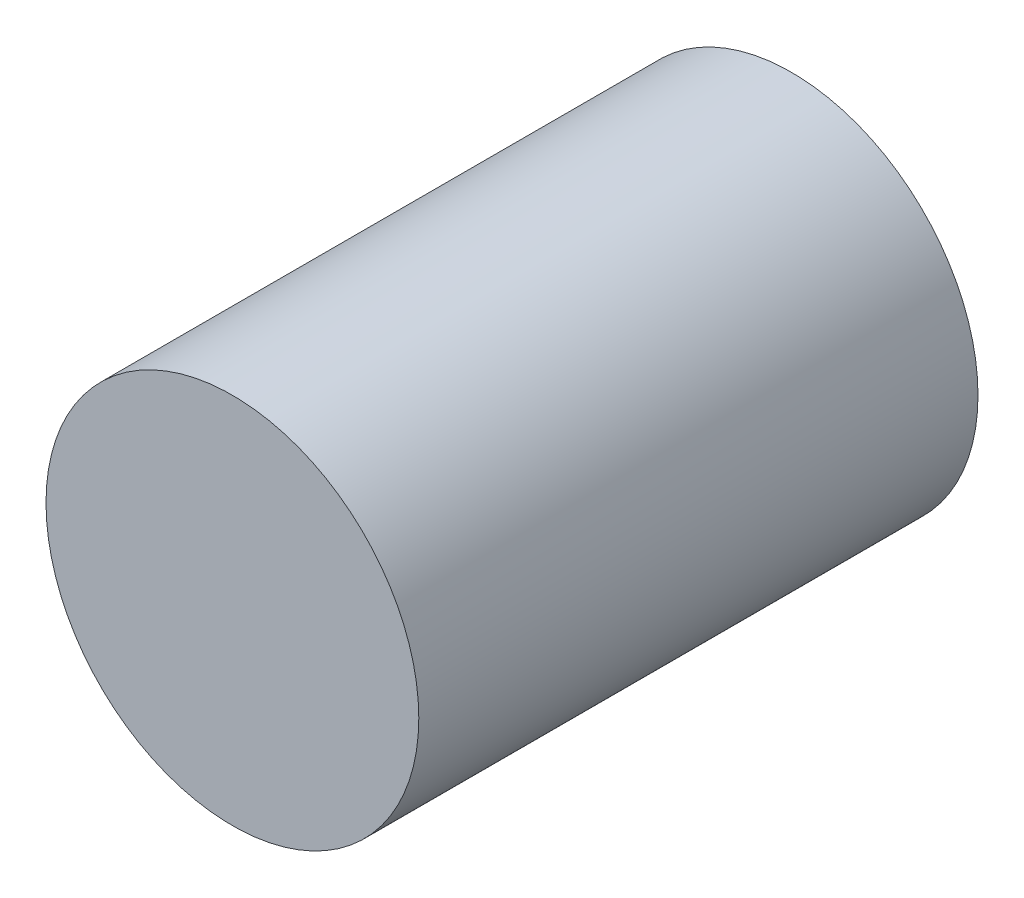
SolidWorks part; units mm, degrees
ref_plane "前视基准面" through (0, 0, 0) normal (0, 0, 1) x (1, 0, 0)
ref_plane "上视基准面" through (0, 0, 0) normal (0, 1, 0) x (1, 0, 0)
ref_plane "右视基准面" through (0, 0, 0) normal (1, 0, 0) x (0, 0, -1)
other "Configuration Table"
sketch "草图1" plane through (0, 0, 0) normal (0, 0, 1) x (1, 0, 0)
  circle A0 centre (0, 0) radius 8
extrude "凸台-拉伸1" add sketch "草图1" along normal blind 24
sketch "草图2" plane through (0, 0, 0) normal (0, 0, 1) x (1, 0, 0)
  circle A0 centre (0, 0) radius 22
sketch "草图3" plane through (0, 0, 0) normal (0, 0, 1) x (1, 0, 0)
  circle A0 centre (0, 0) radius 8
  circle A1 centre (0, 0) radius 22
sketch "草图4" plane through (0, 0, 0) normal (0, 0, 1) x (1, 0, 0)
  arc A0 (4.5201, 2.3619) -> (-5.1, 0) centre (0, 0) cw
sketch "草图5" plane through (0, 0, 0) normal (0, 0, 1) x (1, 0, 0)
  line L0 (18.3379, 4.1145) -> (17.0755, 3.0964)
  arc A0 (21.989, 0) -> (21.117, 6.1312) centre (0, 0) ccw
sketch "草图6" plane through (0, 0, 0) normal (0, 0, 1) x (1, 0, 0)
  line L0 (16.169, 9.5798) -> (15.0558, 9.9878)
  arc A0 (20.6981, 7.4557) -> (18.1979, 12.3627) centre (0, 0) ccw
  arc A1 (15.0558, 9.9878) -> (16.5873, 7.1621) centre (0, 0) ccw
sketch "草图7" plane through (0, 0, 0) normal (0, 0, 1) x (1, 0, 0)
  arc A0 (17.3811, 13.4869) -> (13.4869, 17.3811) centre (0, 0) ccw
  arc A1 (11.5624, 13.4869) -> (13.335, 11.7373) centre (0, 0) ccw
sketch "草图8" plane through (0, 0, 0) normal (0, 0, 1) x (1, 0, 0)
  arc A0 (12.3627, 18.1979) -> (7.4557, 20.6981) centre (0, 0) ccw
  arc A1 (7.4557, 16.0663) -> (9.0284, 15.2382) centre (0, 0) ccw
sketch "草图9" plane through (0, 0, 0) normal (0, 0, 1) x (1, 0, 0)
  arc A0 (6.1342, 21.1275) -> (0, 22) centre (0, 0) ccw
  arc A1 (0, 17.4237) -> (3.8145, 17.001) centre (0, 0) cw
sketch "草图10" plane through (0, 0, 0) normal (0, 0, 1) x (1, 0, 0)
  arc A0 (0, 21.989) -> (-6.1312, 21.117) centre (0, 0) ccw
  arc A1 (-3.8312, 17.0755) -> (0, 17.5) centre (0, 0) ccw
sketch "草图11" plane through (0, 0, 0) normal (0, 0, 1) x (1, 0, 0)
  arc A0 (-7.4557, 20.6981) -> (-12.3627, 18.1979) centre (0, 0) ccw
  arc A1 (-7.4557, 15.0558) -> (-6.66, 15.4243) centre (0, 0) cw
sketch "草图12" plane through (0, 0, 0) normal (0, 0, 1) x (1, 0, 0)
  arc A0 (-13.4869, 17.3811) -> (-17.3811, 13.4869) centre (0, 0) ccw
  arc A1 (-13.4869, 11.5624) -> (-11.7373, 13.335) centre (0, 0) ccw
sketch "草图13" plane through (0, 0, 0) normal (0, 0, 1) x (1, 0, 0)
  line L0 (-16.4574, 7.4557) -> (-15.8845, 8.6091)
  arc A0 (-18.1979, 12.3627) -> (-20.6981, 7.4557) centre (0, 0) ccw
  arc A1 (15.0558, 9.9878) -> (16.5873, 7.1621) centre (0, 0) ccw construction
  arc A2 (-16.4574, 7.4557) -> (-15.8845, 8.6091) centre (0, 0) ccw
sketch "草图14" plane through (0, 0, 0) normal (0, 0, 1) x (1, 0, 0)
  arc A0 (-21.1275, 6.1342) -> (-22, 0) centre (0, 0) ccw
  arc A1 (-17.4237, 0) -> (-17.001, 3.8145) centre (0, 0) cw
sketch "草图15" plane through (0, 0, 0) normal (0, 0, 1) x (1, 0, 0)
  arc A0 (-21.989, 0) -> (-21.117, -6.1312) centre (0, 0) ccw
  arc A1 (-17.0755, -3.8312) -> (-17.5, 0) centre (0, 0) ccw
sketch "草图16" plane through (0, 0, 0) normal (0, 0, 1) x (1, 0, 0)
  arc A0 (-20.6981, -7.4557) -> (-18.1979, -12.3627) centre (0, 0) ccw
  arc A1 (-15.0558, -7.4557) -> (-15.4243, -6.66) centre (0, 0) cw
sketch "草图17" plane through (0, 0, 0) normal (0, 0, 1) x (1, 0, 0)
  arc A0 (-17.3811, -13.4869) -> (-13.4869, -17.3811) centre (0, 0) ccw
  arc A1 (-11.5624, -13.4869) -> (-13.335, -11.7373) centre (0, 0) ccw
sketch "草图18" plane through (0, 0, 0) normal (0, 0, 1) x (1, 0, 0)
  arc A0 (-12.3627, -18.1979) -> (-7.4557, -20.6981) centre (0, 0) ccw
  arc A1 (-7.4557, -16.0663) -> (-9.0284, -15.2382) centre (0, 0) ccw
sketch "草图19" plane through (0, 0, 0) normal (0, 0, 1) x (1, 0, 0)
  arc A0 (-6.1342, -21.1275) -> (0, -22) centre (0, 0) ccw
  arc A1 (0, -17.4237) -> (-3.8145, -17.001) centre (0, 0) cw
sketch "草图20" plane through (0, 0, 0) normal (0, 0, 1) x (1, 0, 0)
  arc A0 (0, -21.989) -> (6.1312, -21.117) centre (0, 0) ccw
  arc A1 (3.8312, -17.0755) -> (0, -17.5) centre (0, 0) ccw
sketch "草图21" plane through (0, 0, 0) normal (0, 0, 1) x (1, 0, 0)
  arc A0 (7.4557, -20.6981) -> (12.3627, -18.1979) centre (0, 0) ccw
  arc A1 (7.4557, -15.0558) -> (6.66, -15.4243) centre (0, 0) cw
sketch "草图22" plane through (0, 0, 0) normal (0, 0, 1) x (1, 0, 0)
  arc A0 (13.4869, -17.3811) -> (17.3811, -13.4869) centre (0, 0) ccw
  arc A1 (13.4869, -11.5624) -> (11.7373, -13.335) centre (0, 0) ccw
sketch "草图23" plane through (0, 0, 0) normal (0, 0, 1) x (1, 0, 0)
  arc A0 (18.1979, -12.3627) -> (20.6981, -7.4557) centre (0, 0) ccw
  arc A1 (16.0663, -7.4557) -> (15.2382, -9.0284) centre (0, 0) ccw
sketch "草图24" plane through (0, 0, 0) normal (0, 0, 1) x (1, 0, 0)
  arc A0 (21.1275, -6.1342) -> (22, 0) centre (0, 0) ccw
  arc A1 (17.4237, 0) -> (17.001, -3.8145) centre (0, 0) cw
